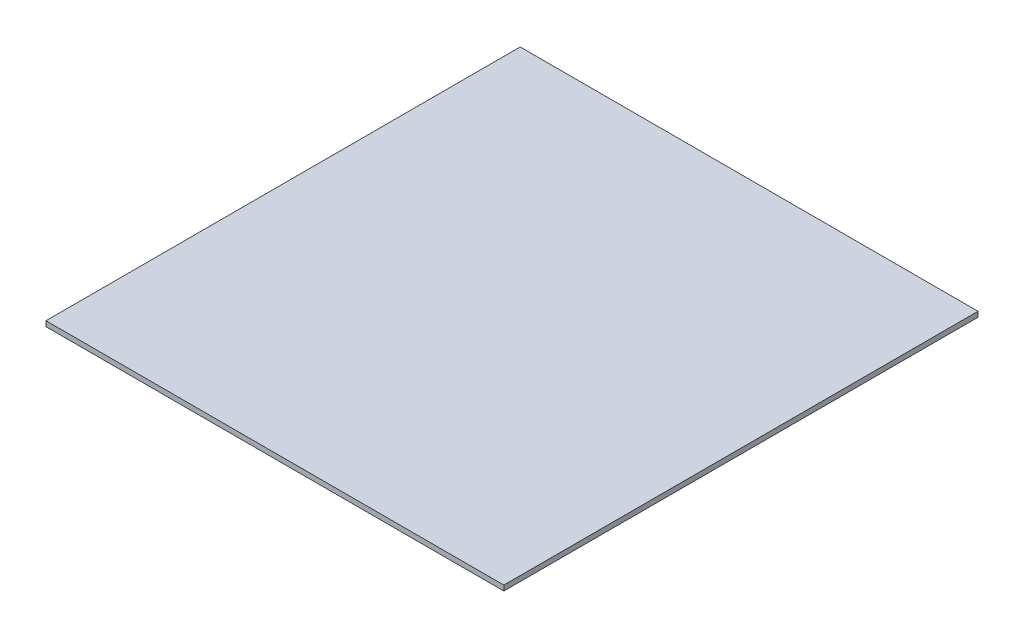
SolidWorks part; units mm, degrees
material "Custom Plastic"
ref_plane "Front Plane" through (0, 0, 0) normal (0, 0, 1) x (1, 0, 0)
ref_plane "Top Plane" through (0, 0, 0) normal (0, 1, 0) x (1, 0, 0)
ref_plane "Right Plane" through (0, 0, 0) normal (1, 0, 0) x (0, 0, -1)
sketch "Sketch1" plane through (0, 0, 0) normal (0, 0, 1) x (1, 0, 0)
  line L1 (-140, 1.5875) -> (140, 1.5875)
  line L2 (-140, 1.5875) -> (-140, -1.5875)
  line L3 (-140, -1.5875) -> (140, -1.5875)
  line L4 (140, 1.5875) -> (140, -1.5875)
  line L5 (-140, 1.5875) -> (140, -1.5875) construction
  line L6 (-140, -1.5875) -> (140, 1.5875) construction
  point P0 (0, 0)
  dimension "D1" = 3.175
  dimension "D2" = 280
extrude "Boss-Extrude1" add sketch "Sketch1" along normal blind 290
